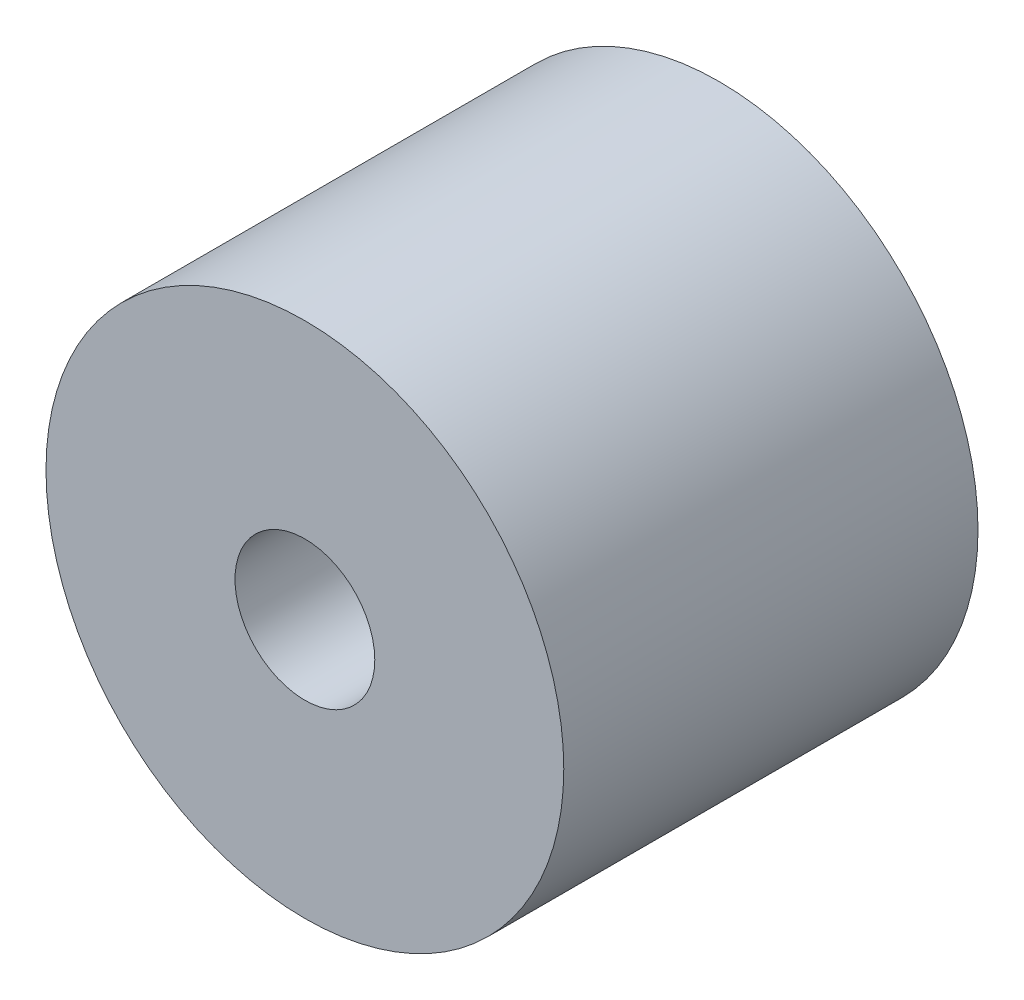
SolidWorks part; units mm, degrees
material "Brass"
ref_plane "Front" through (0, 0, 0) normal (0, 0, 1) x (1, 0, 0)
ref_plane "Top" through (0, 0, 0) normal (0, 1, 0) x (1, 0, 0)
ref_plane "Right" through (0, 0, 0) normal (1, 0, 0) x (0, 0, -1)
sketch "Sketch2" plane through (0, 0, 0) normal (0, 0, 1) x (1, 0, 0)
  circle A0 centre (0, 0) radius 6.35
  dimension "D1" = 12.7
extrude "Boss-Extrude1" add sketch "Sketch2" against normal blind 10.16
hole_wizard "#29 (0.135) Diameter Hole1" positions "Sketch3" profile "Sketch4" hole size "#29" standard "ANSI Inch" end condition through all
sketch "Sketch3" plane through (0, 0, 0) normal (0, 0, 1) x (1, 0, 0)
  point P0 (0, 0)
sketch "Sketch4" plane through (0, 0, 0) normal (1, 0, 0) x (0, -1, 0)
  line L0 (0, 0) -> (0, 10.16)
  line L1 (0, 10.16) -> (1.7145, 10.16)
  line L2 (1.7145, 10.16) -> (1.7145, 0)
  line L5 (1.7145, 0) -> (0, 0)
  line L11 (0, -6.35) -> (0, 107.95) construction
  dimension "Thru Hole Dia." = 3.429
  dimension "Thru Hole Depth" = 10.16
